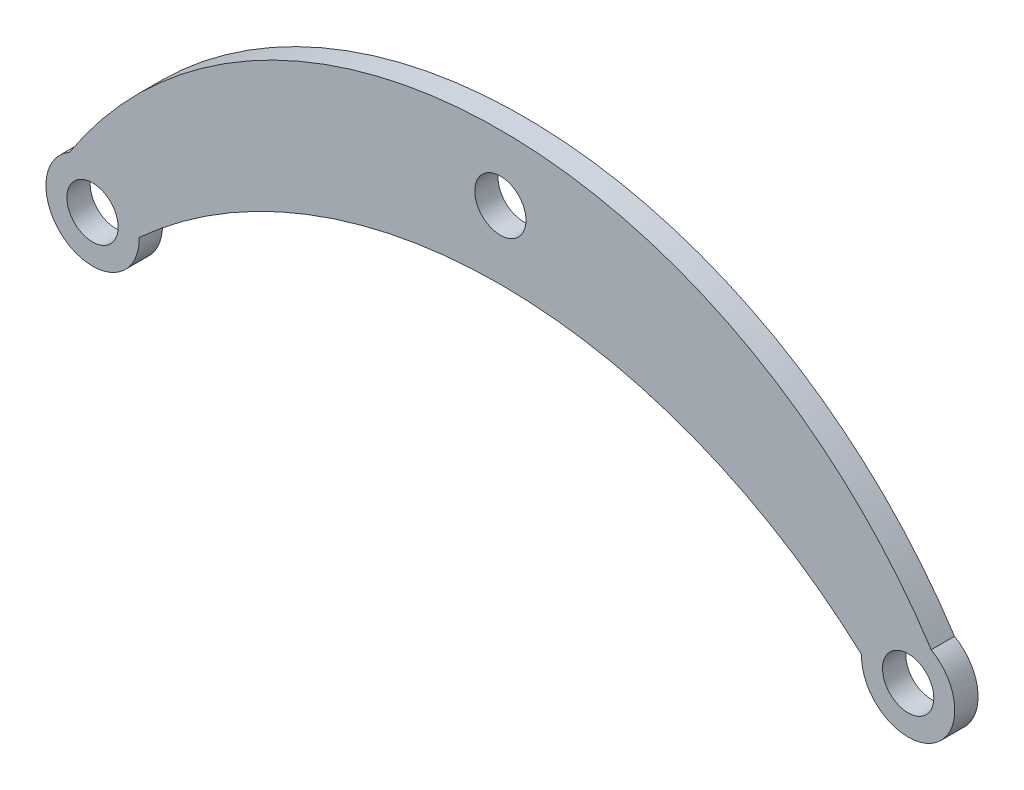
SolidWorks part; units mm, degrees
ref_plane "Front Plane" through (0, 0, 0) normal (0, 0, 1) x (1, 0, 0)
ref_plane "Top Plane" through (0, 0, 0) normal (0, 1, 0) x (1, 0, 0)
ref_plane "Right Plane" through (0, 0, 0) normal (1, 0, 0) x (0, 0, -1)
sketch "Sketch1" plane through (0, 0, 0) normal (0, 0, 1) x (1, 0, 0)
  circle A0 centre (0, 0) radius 11
  circle A1 centre (350, 0) radius 11
  arc A2 (-9.878, 17.3903) -> (19.9888, 0.6682) centre (0, 0) ccw
  arc A3 (330.0112, 0.6682) -> (359.878, 17.3903) centre (350, 0) ccw
  arc A4 (-9.878, 17.3903) -> (359.878, 17.3903) centre (175, -101.8577) cw
  arc A5 (19.9888, 0.6682) -> (330.0112, 0.6682) centre (175, -169.2481) cw
  dimension "D1" = 22
  dimension "D2" = 22
  dimension "D4" = 40
  dimension "D5" = 40
  dimension "D6" = 230
  dimension "D7" = 220
  dimension "D3" = 350
extrude "Boss-Extrude1" add sketch "Sketch1" along normal blind 10
sketch "Sketch3" plane through (0, 0, 10) normal (0, 0, 1) x (1, 0, 0)
  circle A0 centre (175, 90) radius 11
  dimension "D3" = 22
  dimension "D1" = 175
  dimension "D2" = 90
extrude "Cut-Extrude1" cut sketch "Sketch3" against normal blind 10
equation "\"bearing_od\" = 22"
equation "\"wheeldistance\" = 350"
